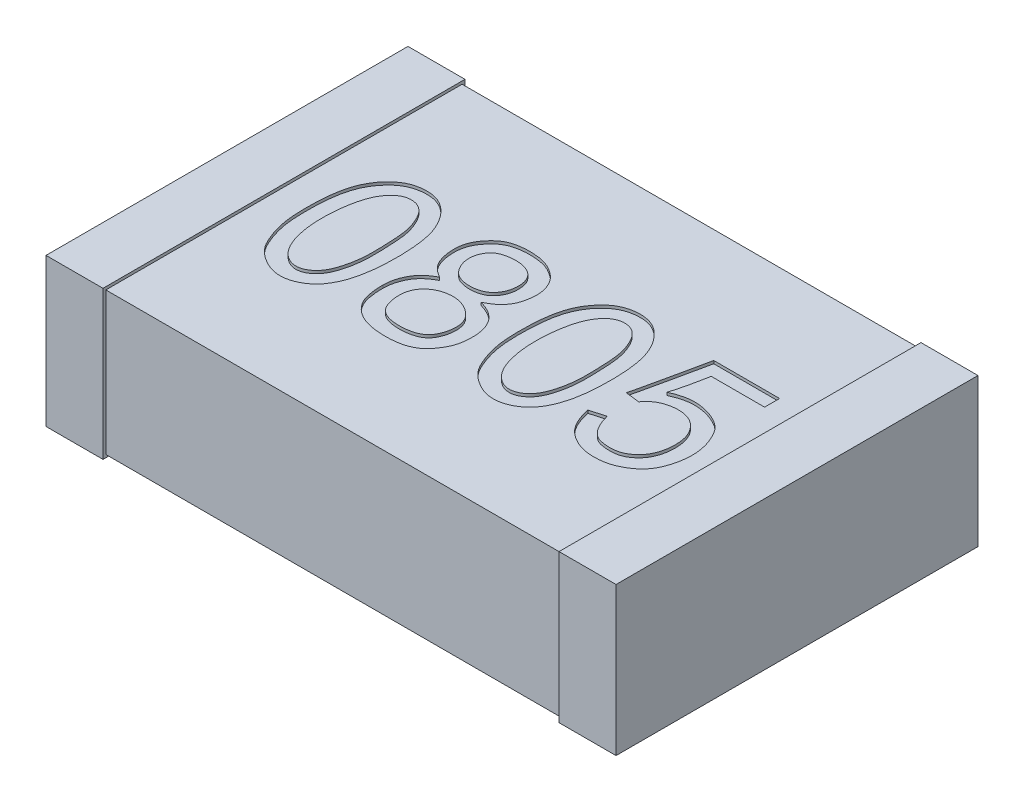
SolidWorks part; units mm, degrees
ref_plane "前视基准面" through (0, 0, 0) normal (0, 0, 1) x (1, 0, 0)
ref_plane "上视基准面" through (0, 0, 0) normal (0, 1, 0) x (1, 0, 0)
ref_plane "右视基准面" through (0, 0, 0) normal (1, 0, 0) x (0, 0, -1)
sketch "草图1" plane through (0, 0, 0) normal (0, 1, 0) x (1, 0, 0)
  line L0 (-31.3913, 0) -> (27.0565, 0) construction
  line L1 (0, 12.4242) -> (0, -8.2436) construction
  line L3 (-1, -0.625) -> (1, -0.625)
  line L4 (-1, -0.625) -> (-1, 0.625)
  line L5 (-1, 0.625) -> (1, 0.625)
  line L6 (1, -0.625) -> (1, 0.625)
  dimension "D1" = 2
  dimension "D2" = 1.25
extrude "凸台-拉伸1" add sketch "草图1" along normal blind 0.5
sketch "草图2" plane through (-1, 0, 0) normal (-1, 0, 0) x (0, 0, 1)
  line L0 (-0.7058, 0.25) -> (0.6827, 0.25) construction
  line L1 (0, -0.0713) -> (0, 0.602) construction
  line L2 (-0.625, 0.5) -> (0.625, 0.5) construction
  line L3 (-0.625, 0) -> (0.625, 0) construction
  line L5 (-0.635, 0.51) -> (0.635, 0.51)
  line L6 (-0.635, 0.51) -> (-0.635, -0.01)
  line L7 (-0.635, -0.01) -> (0.635, -0.01)
  line L8 (0.635, 0.51) -> (0.635, -0.01)
  dimension "D1" = 0.52
  dimension "D2" = 1.27
extrude "凸台-拉伸2" add sketch "草图2" against normal blind 0.2
sketch "草图3" plane through (1, 0, 0) normal (1, 0, 0) x (0, 0, -1)
  line L0 (-0.635, 0.51) -> (0.635, 0.51) construction
  line L1 (-0.635, -0.01) -> (-0.635, 0.51) construction
  line L2 (0.635, -0.01) -> (-0.635, -0.01) construction
  line L3 (0.635, 0.51) -> (0.635, -0.01) construction
  line L4 (-0.635, 0.51) -> (0.635, 0.51)
  line L5 (-0.635, -0.01) -> (-0.635, 0.51)
  line L6 (0.635, -0.01) -> (-0.635, -0.01)
  line L7 (0.635, 0.51) -> (0.635, -0.01)
extrude "凸台-拉伸3" add sketch "草图3" against normal blind 0.2
sketch "草图4" plane through (0, 0.5, 0) normal (0, 1, 0) x (1, 0, 0)
  text T0 "0805" font "黑体" height 0.5
extrude "切除-拉伸1" cut sketch "草图4" against normal blind 0.01
